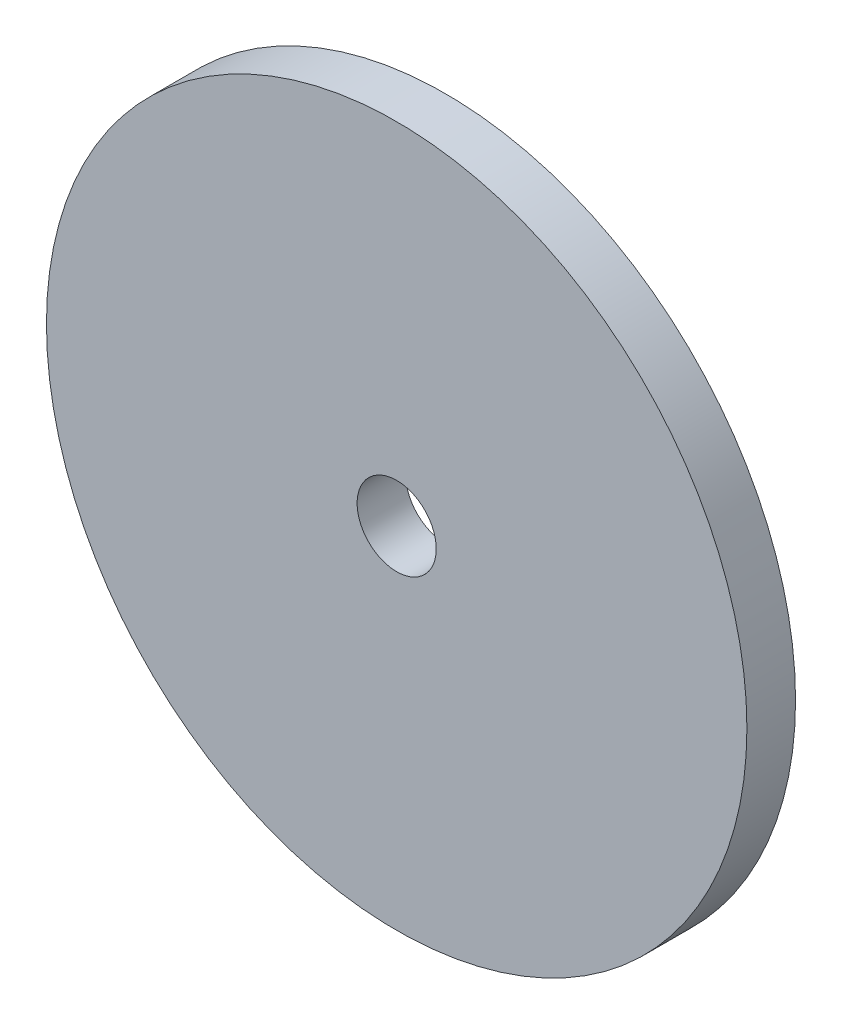
SolidWorks part; units mm, degrees
ref_plane "Front Plane" through (0, 0, 0) normal (0, 0, 1) x (1, 0, 0)
ref_plane "Top Plane" through (0, 0, 0) normal (0, 1, 0) x (1, 0, 0)
ref_plane "Right Plane" through (0, 0, 0) normal (1, 0, 0) x (0, 0, -1)
sketch "Sketch1" plane through (0, 0, 0) normal (0, 0, 1) x (1, 0, 0)
  circle A0 centre (-72.3348, 41.0776) radius 22.86
  circle A1 centre (-72.3348, 41.0776) radius 2.5828
extrude "Boss-Extrude1" add sketch "Sketch1" along normal blind 3.175
